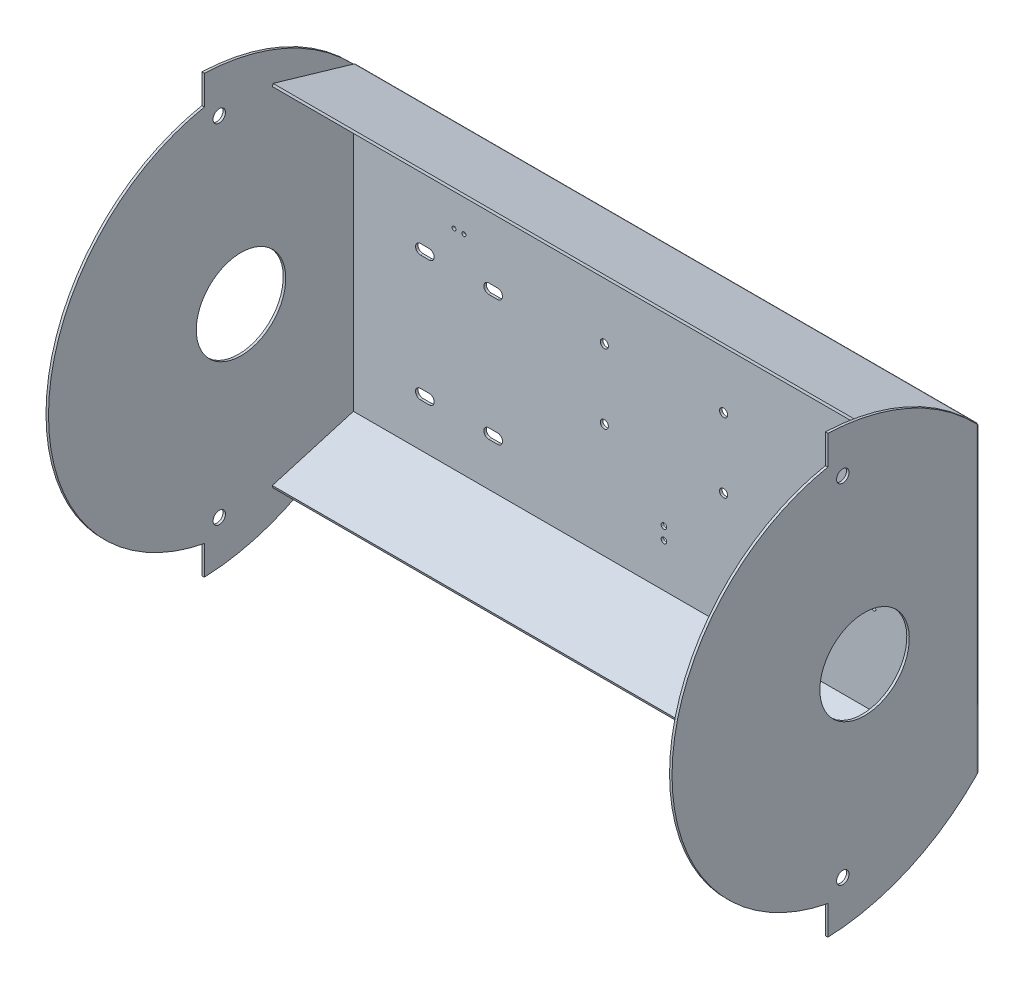
SolidWorks part; units mm, degrees
ref_plane "Plan de face" through (0, 0, 0) normal (0, 0, 1) x (1, 0, 0)
ref_plane "Plan de dessus" through (0, 0, 0) normal (0, 1, 0) x (1, 0, 0)
ref_plane "Plan de droite" through (0, 0, 0) normal (1, 0, 0) x (0, 0, -1)
sketch "Esquisse1" plane through (0, 0, 0) normal (0, 0, 1) x (1, 0, 0)
  line L0 (0, 0) -> (0, 28.6326) construction
  line L1 (-250, 120) -> (250, 120)
  line L2 (-250, 120) -> (-250, -120)
  line L3 (-250, -120) -> (250, -120)
  line L4 (250, 120) -> (250, -120)
  line L5 (0, 0) -> (-48.4845, 0) construction
  dimension "D1" = 500
  dimension "D2" = 240
extrude "Extrusion1" add sketch "Esquisse1" along normal blind 2
sketch "Esquisse2" plane through (-250, 0, 0) normal (-1, 0, 0) x (0, 0, 1)
  line L0 (2, 120) -> (2, -120) construction
  line L1 (0, 0) -> (92.5, 0) construction
  line L2 (0, 120) -> (0, -120) construction
  line L3 (122, -152.1668) -> (122, -175.6986)
  line L4 (122, 152.1668) -> (122, 175.6986)
  line L5 (0, 120) -> (0, -120)
  circle A0 centre (92.5, 0) radius 36
  arc A1 (122, -152.1668) -> (122, 152.1668) centre (92.5, 0) ccw
  arc A2 (122, 175.6986) -> (0, 120) centre (128.5, 0) ccw
  arc A3 (0, -120) -> (122, -175.6986) centre (128.5, 0) ccw
  dimension "D1" = 72
  dimension "D3" = 310
  dimension "D2" = 90.5
  dimension "D4" = 120
extrude "Extrusion2" add sketch "Esquisse2" along normal blind 2
sketch "Esquisse3" plane through (-252, 0, 0) normal (-1, 0, 0) x (0, 0, 1)
  line L0 (0, 0) -> (163.6986, 0) construction
  line L1 (0, 120) -> (0, -120) construction
  circle A0 centre (110, 140) radius 5
  circle A1 centre (110, -140) radius 5
  dimension "D3" = 10
  dimension "D1" = 110
  dimension "D2" = 280
extrude "Enlèv. mat.-Extru.1" cut sketch "Esquisse3" against normal blind 2
mirror "Symétrie1" about plane through (0, 0, 0) normal (1, 0, 0) of "Enlèv. mat.-Extru.1", "Extrusion2"
sketch "Esquisse4" plane through (-250, 0, 0) normal (1, 0, 0) x (0, 0, -1)
  line L0 (-2, -120) -> (-67.2682, -139.0803)
  line L1 (-2, -120) -> (0, -120)
  line L2 (0, -120) -> (0, -121.499)
  line L3 (0, -121.499) -> (-66.707, -141)
  line L4 (-67.2682, -139.0803) -> (-66.707, -141)
  dimension "D1" = 2
  dimension "D2" = 68
  dimension "D3" = 141
extrude "Extrusion3" add sketch "Esquisse4" along normal up to surface (500 mm away) up to face at (250, 135, 110)
mirror "Symétrie2" about plane through (0, 0, 0) normal (0, 1, 0) of "Extrusion3"
fillet "Congé1" radius 2 4 edges at (0, 121.499, 0) (0, -121.499, 0) (-252, 0, 0) (252, 0, 0)
sketch "Esquisse5" plane through (0, 0, 2) normal (0, 0, 1) x (1, 0, 0)
  line L0 (0, 0) -> (52.4324, 0) construction
  line L1 (0, 0) -> (0, 74.0541) construction
  circle A0 centre (-48, 28) radius 3.25
  circle A1 centre (48, 28) radius 3.25
  circle A2 centre (48, -28) radius 3.25
  circle A3 centre (-48, -28) radius 3.25
  dimension "D3" = 6.5
  dimension "D1" = 96
  dimension "D2" = 56
extrude "Enlèv. mat.-Extru.2" cut sketch "Esquisse5" against normal blind 2
sketch "Esquisse6" plane through (0, 0, 2) normal (0, 0, 1) x (1, 0, 0)
  line L0 (250, 30.5) -> (109.5506, 30.5) construction
  line L1 (250, -120) -> (250, 120) construction
  line L2 (0, 0) -> (232.4324, 0) construction
  line L3 (189, 85) -> (196, 85)
  line L4 (189, 77) -> (196, 77)
  arc A0 (196, 77) -> (196, 85) centre (196, 81) ccw
  arc A1 (189, 85) -> (189, 77) centre (189, 81) ccw
  dimension "D2" = 8
  dimension "D1" = 30.5
  dimension "D3" = 7
  dimension "D4" = 101
  dimension "D5" = 54
extrude "Enlèv. mat.-Extru.3" cut sketch "Esquisse6" against normal blind 2
pattern_linear "Répétition linéaire1" count 2 spacing 101 along (0, -1, 0) count 2 spacing 55 along (-1, 0, 0) of "Enlèv. mat.-Extru.3"
sketch "Esquisse7" plane through (0, 0, 2) normal (0, 0, 1) x (1, 0, 0)
  line L0 (-196, -77) -> (-189, -77)
  line L1 (-189, -85) -> (-196, -85)
  line L2 (-250, 120) -> (-250, -120) construction
  line L3 (-196, -30.5) -> (-102.028, -30.5) construction
  arc A0 (-196, -77) -> (-196, -85) centre (-196, -81) ccw
  arc A1 (-189, -85) -> (-189, -77) centre (-189, -81) ccw
  dimension "D1" = 8
  dimension "D2" = 54
  dimension "D3" = 7
  dimension "D4" = 30.5
  dimension "D5" = 101
extrude "Enlèv. mat.-Extru.4" cut sketch "Esquisse7" against normal blind 2
pattern_linear "Répétition linéaire2" count 2 spacing 55 along (1, 0, 0) count 2 spacing 101 along (0, 1, 0) of "Enlèv. mat.-Extru.4"
sketch "Esquisse8" plane through (0, 0, 2) normal (0, 0, 1) x (1, 0, 0)
  line L0 (-241, 87.5) -> (-71, 87.5) construction
  line L1 (-250, 120) -> (-250, -120) construction
  line L2 (250, 120) -> (-250, 120) construction
  circle A0 centre (-241, 87.5) radius 2.75
  circle A1 centre (-71, 87.5) radius 2.75
  dimension "D1" = 5.5
  dimension "D2" = 9
  dimension "D3" = 32.5
  dimension "D4" = 170
extrude "Enlèv. mat.-Extru.5" cut sketch "Esquisse8" against normal blind 2
sketch "Esquisse9" plane through (0, 0, 2) normal (0, 0, 1) x (1, 0, 0)
  line L0 (241, -87.5) -> (71, -87.5) construction
  line L1 (-250, -120) -> (250, -120) construction
  line L2 (250, -120) -> (250, 120) construction
  circle A0 centre (71, -87.5) radius 2.75
  circle A1 centre (241, -87.5) radius 2.75
  dimension "D3" = 5.5
  dimension "D1" = 170
  dimension "D2" = 32.5
  dimension "D4" = 9
extrude "Enlèv. mat.-Extru.6" cut sketch "Esquisse9" against normal blind 2
sketch "Esquisse10" plane through (0, 0, 2) normal (0, 0, 1) x (1, 0, 0)
  line L0 (-165, -31.3514) -> (-165, 105.4054) construction
  line L1 (165, 16.7568) -> (165, -87.5676) construction
  line L2 (-250, -120) -> (250, -120) construction
  line L3 (250, 120) -> (-250, 120) construction
  arc A0 (-189, 16) -> (-189, 24) centre (-189, 20) ccw construction
  arc A1 (-141, 24) -> (-141, 16) centre (-141, 20) ccw construction
  arc A2 (141, -24) -> (141, -16) centre (141, -20) ccw construction
  arc A3 (189, -16) -> (189, -24) centre (189, -20) ccw construction
  circle A4 centre (-169, 48) radius 1.6
  circle A5 centre (-161, 48) radius 1.6
  circle A6 centre (161, -48) radius 1.6
  circle A7 centre (169, -48) radius 1.6
  dimension "D1" = 3.2
  dimension "D2" = 72
  dimension "D3" = 72
  dimension "D4" = 8
  dimension "D5" = 8
extrude "Enlèv. mat.-Extru.7" cut sketch "Esquisse10" against normal through all
sketch "Esquisse11" plane through (0, 0, 2) normal (0, 0, 1) x (1, 0, 0)
  line L0 (0, 0) -> (0, -120) construction
  line L1 (-250, -120) -> (250, -120) construction
  circle A0 centre (0, -75) radius 2.25
  circle A1 centre (0, -85) radius 2.25
  dimension "D1" = 4.5
  dimension "D2" = 10
  dimension "D3" = 35
extrude "Enlèv. mat.-Extru.8" cut sketch "Esquisse11" against normal blind 10
